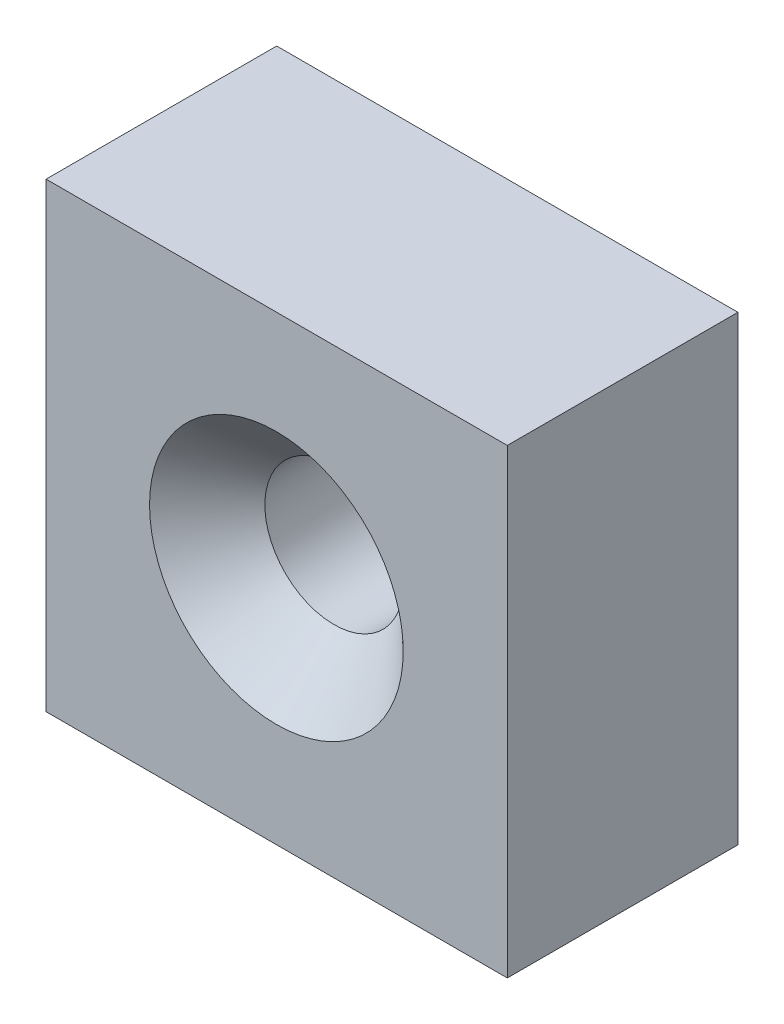
SolidWorks part; units mm, degrees
ref_plane "前视基准面" through (0, 0, 0) normal (0, 0, 1) x (1, 0, 0)
ref_plane "上视基准面" through (0, 0, 0) normal (0, 1, 0) x (1, 0, 0)
ref_plane "右视基准面" through (0, 0, 0) normal (1, 0, 0) x (0, 0, -1)
other "Configuration Table"
sketch "草图1" plane through (0, 0, 0) normal (0, 0, 1) x (1, 0, 0)
  line L1 (0, 0) -> (20, 0)
  line L2 (0, 0) -> (0, 20)
  line L3 (0, 20) -> (20, 20)
  line L4 (20, 0) -> (20, 20)
extrude "BaseBox" add sketch "草图1" along normal blind 10
hole_wizard "Hole_cs_iso_flathead_m6" positions "草图3" profile "草图2" countersink size "M6" standard "ISO" end condition through all
sketch "草图3" plane through (0, 0, 10) normal (0, 0, 1) x (1, 0, 0)
  point P0 (9.9865, 10.0143)
sketch "草图2" plane through (9.9865, 10.0143, 10) normal (1, 0, 0) x (0, -1, 0)
  line L0 (0, 0) -> (0, 10)
  line L1 (0, 10) -> (3, 10)
  line L2 (3, 10) -> (3, 2.5)
  line L3 (3, 2.5) -> (5.5, 0)
  line L5 (5.5, 0) -> (0, 0)
  line L6 (-3, 2.5) -> (-5.5, 0) construction
  line L11 (0, -6.35) -> (0, 107.95) construction
  dimension "通孔孔直径" = 6
  dimension "通孔孔深度" = 10
  dimension "近端锥形沉头孔直径" = 11
  dimension "近端锥形沉头孔角度" = 90
